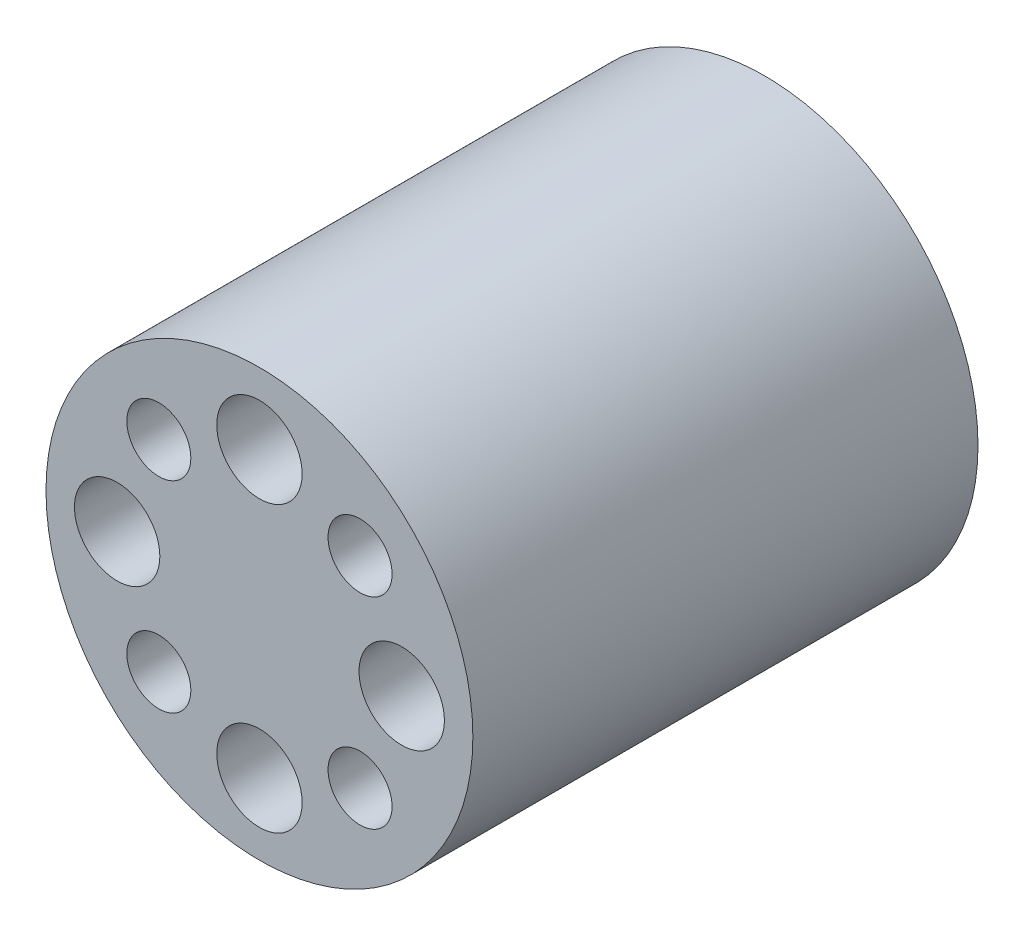
SolidWorks part; units mm, degrees
ref_plane "Ebene vorne" through (0, 0, 0) normal (0, 0, 1) x (1, 0, 0)
ref_plane "Ebene oben" through (0, 0, 0) normal (0, 1, 0) x (1, 0, 0)
ref_plane "Ebene rechts" through (0, 0, 0) normal (1, 0, 0) x (0, 0, -1)
sketch "Skizze1" plane through (0, 0, 0) normal (0, 0, 1) x (1, 0, 0)
  circle A7 centre (0, 0) radius 15
  circle A8 centre (0, 0) radius 10
  circle A9 centre (0, -10) radius 1.65
  circle A10 centre (-10, 0) radius 1.65
  circle A11 centre (0, 10) radius 1.65
  circle A12 centre (10, 0) radius 1.65
  point P15 (0, 0)
  dimension "D1" = 30
  dimension "D2" = 4
  dimension "D3" = 20
  dimension "D4" = 3.3
extrude "Aufsatz-Linear austragen1" add sketch "Skizze1" along normal blind 35.5 contours A12 A8 A11 A10 A9 | A7 A12 A8 A9 A10 A11
sketch "Skizze3" plane through (0, 0, 35.5) normal (0, 0, 1) x (1, 0, 0)
  circle A0 centre (0, 10) radius 3
  circle A1 centre (10, 0) radius 3
  circle A2 centre (0, -10) radius 3
  circle A3 centre (-10, 0) radius 3
  circle A4 centre (0, 0) radius 10
  point P5 (0, 0)
  point P12 (0, 0)
  point P14 (0, 0)
  circle M2 centre (0, 10) radius 1.65
  circle M3 centre (-10, 0) radius 1.65
  circle M4 centre (0, -10) radius 1.65
  circle M5 centre (10, 0) radius 1.65
  dimension "D1" = 4
  dimension "D2" = 6
sketch "Skizze4" plane through (0, 0, 35.5) normal (0, 0, 1) x (1, 0, 0)
  line L0 (0, 0) -> (7.0711, 7.0711) construction
  circle A0 centre (0, 0) radius 10
  circle A1 centre (7.0711, 7.0711) radius 2.25
  circle A2 centre (7.0711, -7.0711) radius 2.25
  circle A3 centre (-7.0711, -7.0711) radius 2.25
  circle A4 centre (-7.0711, 7.0711) radius 2.25
  point P6 (0, 0)
  point P15 (0, 0)
  dimension "D1" = 4.5
extrude "Schnitt-Linear austragen2" cut sketch "Skizze4" against normal blind 10 contours A0 A4 | A0 A4 | A1 | A2 | A3
extrude "Schnitt-Linear austragen3" cut sketch "Skizze3" against normal offset from surface (29.5 mm away) 6 contours A4 A0 M2 | A0 A4 M2 | A4 A1 M5 | A4 A1 M5 | A2 A4 M4 | A4 A2 M4 | A3 A4 M3 | A4 A3 M3
